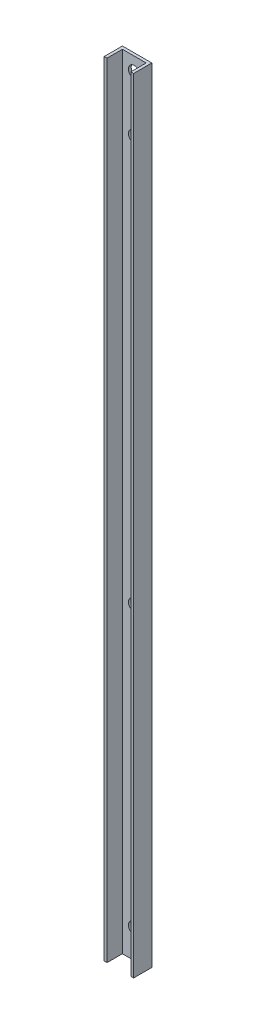
SolidWorks part; units mm, degrees
ref_plane "Front Plane" through (0, 0, 0) normal (0, 0, 1) x (1, 0, 0)
ref_plane "Top Plane" through (0, 0, 0) normal (0, 1, 0) x (1, 0, 0)
ref_plane "Right Plane" through (0, 0, 0) normal (1, 0, 0) x (0, 0, -1)
sketch "Sketch1" plane through (0, 0, 0) normal (0, 1, 0) x (1, 0, 0)
  line L0 (-3.47, -1.8133) -> (-3.47, 4.6867)
  line L1 (-3.47, 4.6867) -> (7.03, 4.6867)
  line L2 (7.03, 4.6867) -> (7.03, -1.8133)
  dimension "D1" = 10.5
  dimension "D2" = 6.5
  dimension "D3" = 6.5
extrude "Extrude-Thin1" add sketch "Sketch1" along normal blind 280 thin
sketch "Sketch2" plane through (0, 0, -4.6867) normal (0, 0, -1) x (-1, 0, 0)
  circle A0 centre (-1.78, 275) radius 2.1
  circle A1 centre (-1.78, 255) radius 2.1
  circle A4 centre (-1.78, 110) radius 2.1
  circle A5 centre (-1.78, 10) radius 2.1
  dimension "D1" = 4.2
  dimension "D2" = 4.2
extrude "Cut-Extrude1" cut sketch "Sketch2" against normal blind 10
